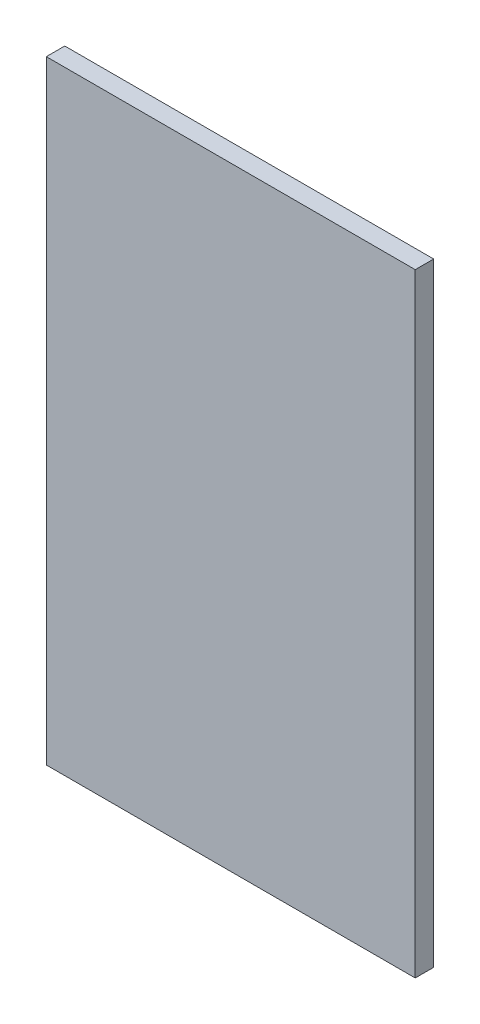
SolidWorks part; units mm, degrees
material "Air"
ref_plane "Front Plane" through (0, 0, 0) normal (0, 0, 1) x (1, 0, 0)
ref_plane "Top Plane" through (0, 0, 0) normal (0, 1, 0) x (1, 0, 0)
ref_plane "Right Plane" through (0, 0, 0) normal (1, 0, 0) x (0, 0, -1)
sketch "Sketch1" plane through (0, 0, 0) normal (0, 0, 1) x (1, 0, 0)
  line L0 (0, 0) -> (1000, 0)
  line L1 (1000, 0) -> (1000, 1662.9)
  line L2 (1000, 1662.9) -> (0, 1662.9)
  line L3 (0, 1662.9) -> (0, 0)
  dimension "D1" = 1662.9
  dimension "D2" = 1000
extrude "Boss-Extrude1" add sketch "Sketch1" along normal blind 50
